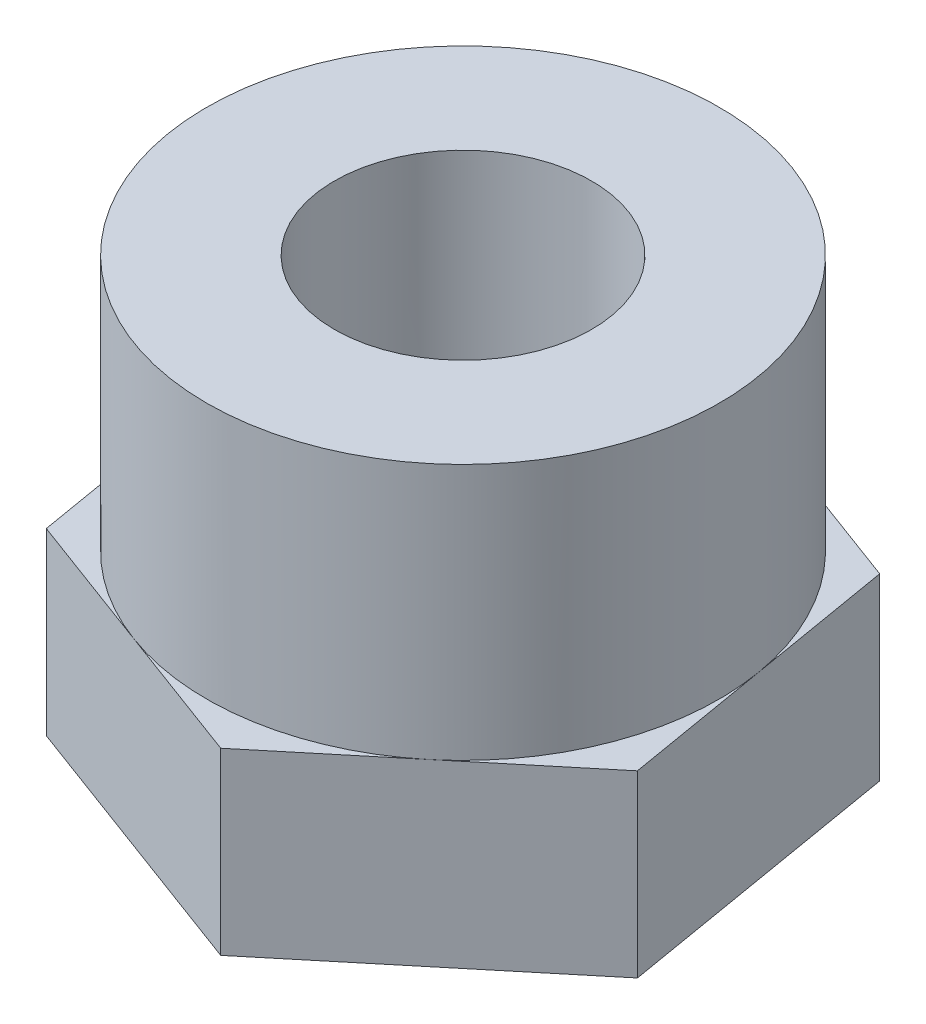
SolidWorks part; units mm, degrees
ref_plane "Front Plane" through (0, 0, 0) normal (0, 0, 1) x (1, 0, 0)
ref_plane "Top Plane" through (0, 0, 0) normal (0, 1, 0) x (1, 0, 0)
ref_plane "Right Plane" through (0, 0, 0) normal (1, 0, 0) x (0, 0, -1)
sketch "Sketch1" plane through (0, 0, 0) normal (0, 1, 0) x (1, 0, 0)
  circle A0 centre (0, 0) radius 12.7
  dimension "D1" = 25.4
extrude "Boss-Extrude1" add sketch "Sketch1" along normal blind 12.7
sketch "Sketch2" plane through (0, 0, 0) normal (0, -1, 0) x (-1, 0, 0)
  line L1 (-11.2948, 9.3531) -> (-13.7474, -5.105)
  line L2 (-13.7474, -5.105) -> (-2.4526, -14.4581)
  line L3 (-2.4526, -14.4581) -> (11.2948, -9.3531)
  line L4 (11.2948, -9.3531) -> (13.7474, 5.105)
  line L5 (13.7474, 5.105) -> (2.4526, 14.4581)
  line L6 (2.4526, 14.4581) -> (-11.2948, 9.3531)
  circle A0 centre (0, 0) radius 12.7 construction
  dimension "D1" = 25.4
extrude "Boss-Extrude2" add sketch "Sketch2" along normal blind 8.89
sketch "Sketch3" plane through (0, 0, 0) normal (0, 0, 1) x (1, 0, 0)
  line L0 (0, -8.89) -> (0, -15.645)
  line L1 (2.4526, -8.89) -> (-11.2948, -8.89) construction
  line L2 (0, -15.645) -> (-1, -15.645)
  line L3 (-12.7, -8.89) -> (0, -8.89)
  line L4 (-1, -15.645) -> (-12.7, -8.89)
  line L5 (-12.7, -8.89) -> (-12.847, -8.8058)
  dimension "D1" = 1
  dimension "D2" = 12.7
  dimension "D3" = 30
revolve "Revolve1" add sketch "Sketch3" angle 360 about L0
sketch "Sketch4" plane through (0, -15.645, 0) normal (0, -1, 0) x (1, 0, 0)
  circle A0 centre (0, 0) radius 0.6
  dimension "D1" = 1.2
extrude "Cut-Extrude1" cut sketch "Sketch4" against normal up to next
sketch "Sketch5" plane through (0, 12.7, 0) normal (0, 1, 0) x (1, 0, 0)
  circle A0 centre (0, 0) radius 6.3754
  dimension "D1" = 12.7508
extrude "Cut-Extrude2" cut sketch "Sketch5" against normal blind 11.8313
sketch "Sketch6" plane through (0, 0, 0) normal (0, 0, 1) x (1, 0, 0)
  line L0 (0, 0.8687) -> (6.3754, 0.8687)
  line L1 (0, 0.8687) -> (0, -16.6476)
  line L2 (0, -16.6476) -> (6.3754, 0.8687)
  dimension "D1" = 20
revolve "Cut-Revolve1" cut sketch "Sketch6" angle 360 about L1
